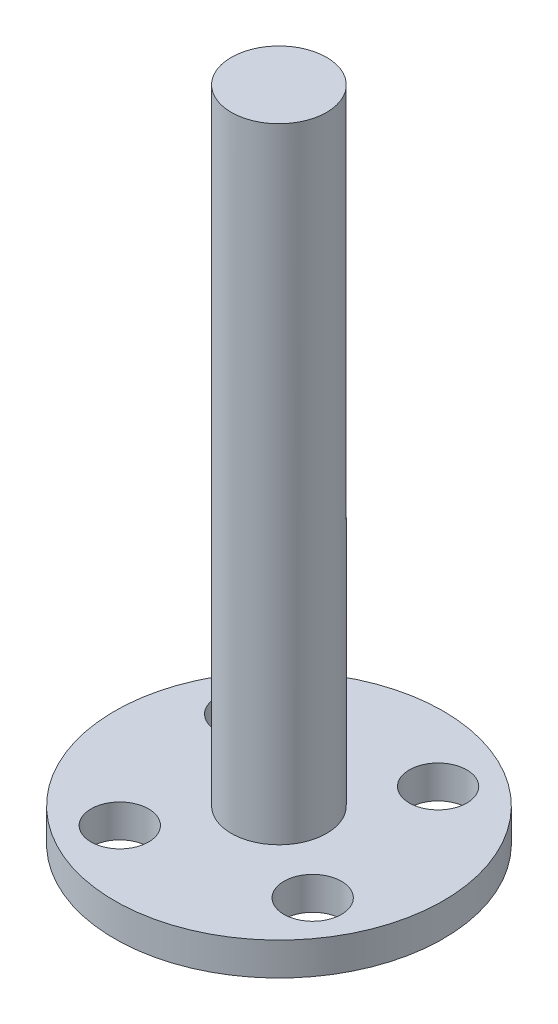
SolidWorks part; units mm, degrees
ref_plane "前视基准面" through (0, 0, 0) normal (0, 0, 1) x (1, 0, 0)
ref_plane "上视基准面" through (0, 0, 0) normal (0, 1, 0) x (1, 0, 0)
ref_plane "右视基准面" through (0, 0, 0) normal (1, 0, 0) x (0, 0, -1)
other "Configuration Table"
sketch "草图1" plane through (0, 0, 0) normal (0, 1, 0) x (1, 0, 0)
  circle A0 centre (0, 0) radius 2.9
  dimension "D1" = 5.8
extrude "凸台-拉伸1" add sketch "草图1" along normal blind 40
sketch "草图2" plane through (0, 0, 0) normal (0, -1, 0) x (1, 0, 0)
  circle A0 centre (0, 0) radius 10
  dimension "D1" = 20
extrude "凸台-拉伸2" add sketch "草图2" against normal blind 2
sketch "草图3" plane through (0, 2, 0) normal (0, 1, 0) x (1, 0, 0)
  circle A1 centre (-3.8145, -5.8694) radius 1.75
  circle A2 centre (-5.8694, 3.8145) radius 1.75
  circle A3 centre (3.8145, 5.8694) radius 1.75
  circle A4 centre (5.8694, -3.8145) radius 1.75
  point P12 (0, 0)
  dimension "D1" = 3.5
  dimension "D2" = 4
extrude "切除-拉伸1" cut sketch "草图3" against normal blind 3
